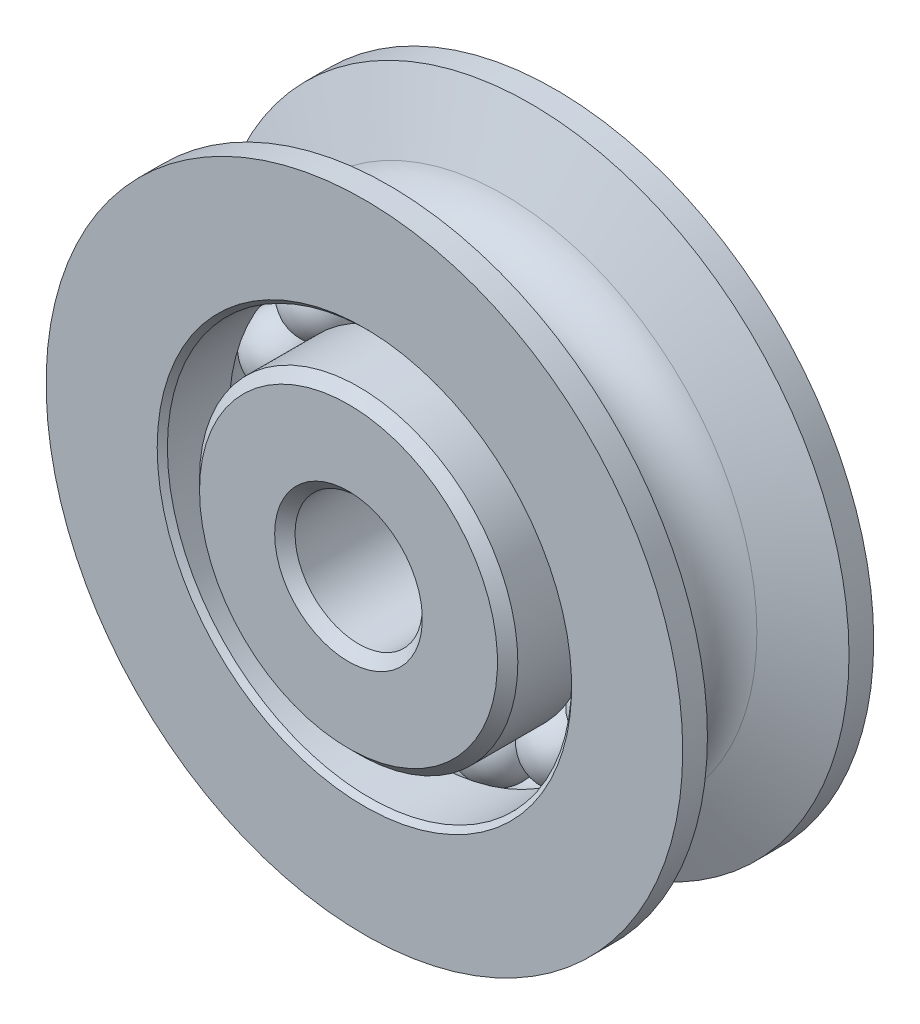
SolidWorks part; units mm, degrees
ref_plane "Front" through (0, 0, 0) normal (0, 0, 1) x (1, 0, 0)
ref_plane "Top" through (0, 0, 0) normal (0, 1, 0) x (1, 0, 0)
ref_plane "Right" through (0, 0, 0) normal (1, 0, 0) x (0, 0, -1)
sketch "Sketch1" plane through (0, 0, 0) normal (1, 0, 0) x (0, 0, -1)
  line L0 (3.5306, 15.875) -> (4.7625, 15.875)
  line L1 (-3.5306, 15.875) -> (-4.7625, 15.875)
  line L2 (-3.5306, 15.875) -> (-2.2078, 12.6016)
  line L3 (1.4287, 10.0806) -> (4.7625, 10.0806)
  line L4 (5.5562, 3.175) -> (-5.5562, 3.175)
  line L5 (-1.4287, 7.9375) -> (-5.5563, 7.9375)
  line L6 (3.5306, 15.875) -> (2.2078, 12.6016)
  line L8 (-5.5562, 0) -> (5.5562, 0) construction
  line L10 (4.7625, 15.875) -> (4.7625, 10.0806)
  line L13 (-5.5563, 7.9375) -> (-5.5562, 3.175)
  line L14 (0, 11.1125) -> (0, -11.1125) construction
  line L16 (5.5563, 7.9375) -> (5.5562, 3.175)
  line L17 (-4.7625, 15.875) -> (-4.7625, -15.875) construction
  line L18 (-4.7625, 10.0806) -> (-1.4287, 10.0806)
  line L20 (5.5563, 7.9375) -> (1.4287, 7.9375)
  line L21 (-4.7625, 10.0806) -> (-4.7625, 15.875)
  arc A0 (-2.2078, 12.6016) -> (2.2078, 12.6016) centre (0, 13.4938) ccw
  circle A1 centre (0, 13.4938) radius 2.3813 construction
  circle A2 centre (0, 0) radius 3.175 construction
  circle A3 centre (0, 0) radius 7.9375 construction
  arc A4 (-1.4287, 7.9375) -> (1.4287, 7.9375) centre (0, 9.0091) ccw
  circle A5 centre (0, -13.4937) radius 2.3813 construction
  arc A6 (1.4287, 10.0806) -> (-1.4287, 10.0806) centre (0, 9.0091) ccw
  point P28 (-4.7625, 0)
  dimension "Rope Dia" = 4.7625
  dimension "Shaft Dia" = 6.35
  dimension "D1" = 15.875
  dimension "D2" = 3.5719
  dimension "Wd" = 11.1125
  dimension "D8" = 1.2319
  dimension "Groove Dia" = 22.225
  dimension "OD" = 31.75
  dimension "w Wd" = 9.525
  dimension "D3" = 2.1431
revolve "Revolve1" add sketch "Sketch1" angle 360 about L8
sketch "Sketch2" plane through (0, 0, 0) normal (1, 0, 0) x (0, 0, -1)
  line L0 (0, 11.1125) -> (0, -11.1125) construction
  line L1 (0, 10.795) -> (0, 7.2231)
  arc A0 (1.4287, 10.0806) -> (-1.4287, 10.0806) centre (0, 9.0091) ccw construction
  arc A1 (0, 7.2231) -> (0, 10.795) centre (0, 9.0091) ccw
revolve "Revolve2" add sketch "Sketch2" angle 360 about L1
pattern_circular "CirPattern1" count 15 over 360 about axis through (0, 0, 0) along (0, 0, 1) of bodies 117
chamfer "Chamfer1" distance 0.508 angle 45 4 edges at (3.175, 0, -5.5562) (7.9375, 0, -5.5563) (7.9375, 0, 5.5563) (3.175, 0, 5.5562)
chamfer "Chamfer2" distance 0.254 angle 45 2 edges at (10.0806, 0, -4.7625) (10.0806, 0, 4.7625)
equation "\"D1@Sketch1\" = \"Shaft Dia@Sketch1\" * 2.5"
equation "\"D2@Sketch1\" = \"Rope Dia@Sketch1\" * .75"
equation "\"D3@Sketch1\" = \"D2@Sketch1\" * .6"
